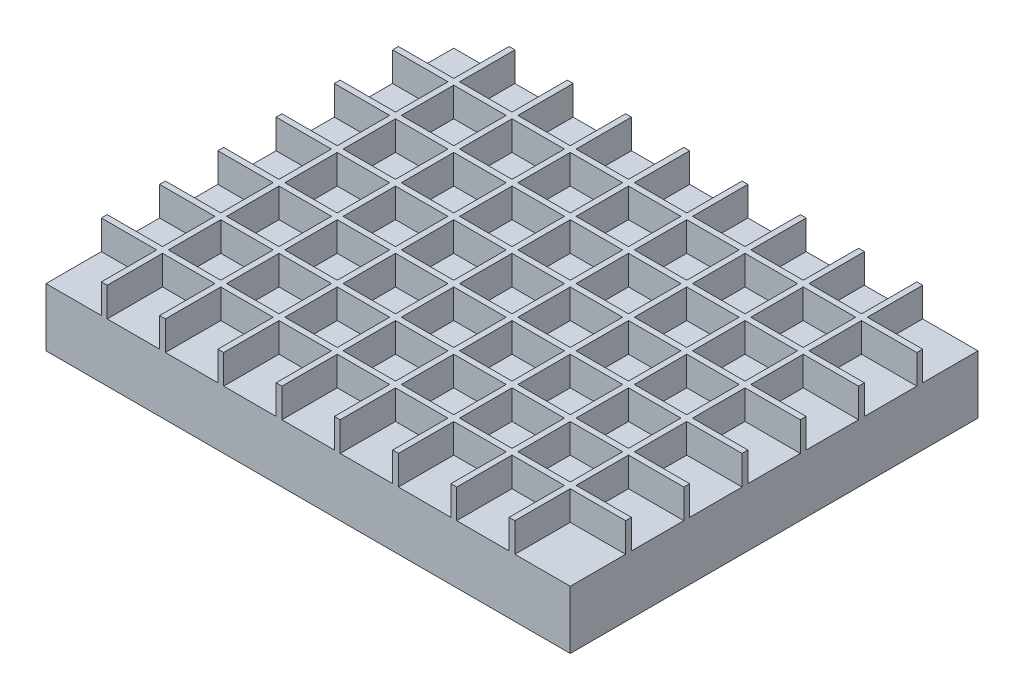
SolidWorks part; units mm, degrees
ref_plane "Front Plane" through (0, 0, 0) normal (0, 0, 1) x (1, 0, 0)
ref_plane "Top Plane" through (0, 0, 0) normal (0, 1, 0) x (1, 0, 0)
ref_plane "Right Plane" through (0, 0, 0) normal (1, 0, 0) x (0, 0, -1)
sketch "Sketch1" plane through (0, 0, 0) normal (0, 1, 0) x (1, 0, 0)
  line L1 (-45, 35) -> (45, 35)
  line L2 (-45, 35) -> (-45, -35)
  line L3 (-45, -35) -> (45, -35)
  line L4 (45, 35) -> (45, -35)
  line L5 (-45, 35) -> (45, -35) construction
  line L6 (-45, -35) -> (45, 35) construction
  point P0 (0, 0)
  dimension "D1" = 70
  dimension "D2" = 90
extrude "Boss-Extrude1" add sketch "Sketch1" along normal blind 10
shell "Shell3" thickness 1
sketch "Sketch2" plane through (0, 10, 0) normal (0, 1, 0) x (1, 0, 0)
  line L0 (-35, 35) -> (-35, -35) construction
  line L1 (45, 35) -> (-45, 35) construction
  line L2 (-45, -35) -> (45, -35) construction
  line L3 (-45, 35) -> (-45, -35) construction
  line L5 (-35.5, 35) -> (-34.5, 35)
  line L6 (-35.5, 35) -> (-35.5, -35)
  line L7 (-35.5, -35) -> (-34.5, -35)
  line L8 (-34.5, 35) -> (-34.5, -35)
  line L9 (-35.5, 35) -> (-34.5, -35) construction
  line L10 (-35.5, -35) -> (-34.5, 35) construction
  point P8 (-35, 0)
  dimension "D1" = 10
  dimension "D2" = 1
extrude "Boss-Extrude2" add sketch "Sketch2" along normal blind 5
pattern_linear "LPattern1" count 8 spacing 10 along (1, 0, 0) of "Boss-Extrude2"
sketch "Sketch3" plane through (0, 10, 0) normal (0, 1, 0) x (1, 0, 0)
  line L0 (-45, 25) -> (45, 25) construction
  line L1 (-45, 35) -> (-45, -35) construction
  line L2 (45, -35) -> (45, 35) construction
  line L3 (45, 35) -> (35.5, 35) construction
  line L5 (-45, 25.5) -> (45, 25.5)
  line L6 (-45, 25.5) -> (-45, 24.5)
  line L7 (-45, 24.5) -> (45, 24.5)
  line L8 (45, 25.5) -> (45, 24.5)
  line L9 (-45, 25.5) -> (45, 24.5) construction
  line L10 (-45, 24.5) -> (45, 25.5) construction
  point P8 (0, 25)
  dimension "D1" = 10
  dimension "D2" = 1
extrude "Boss-Extrude3" add sketch "Sketch3" along normal blind 5
pattern_linear "LPattern2" count 6 spacing 10 along (0, 0, 1) of "Boss-Extrude3"
sketch "Sketch4" plane through (0, 10, 0) normal (0, 1, 0) x (1, 0, 0)
  point P0 (0, 0)
